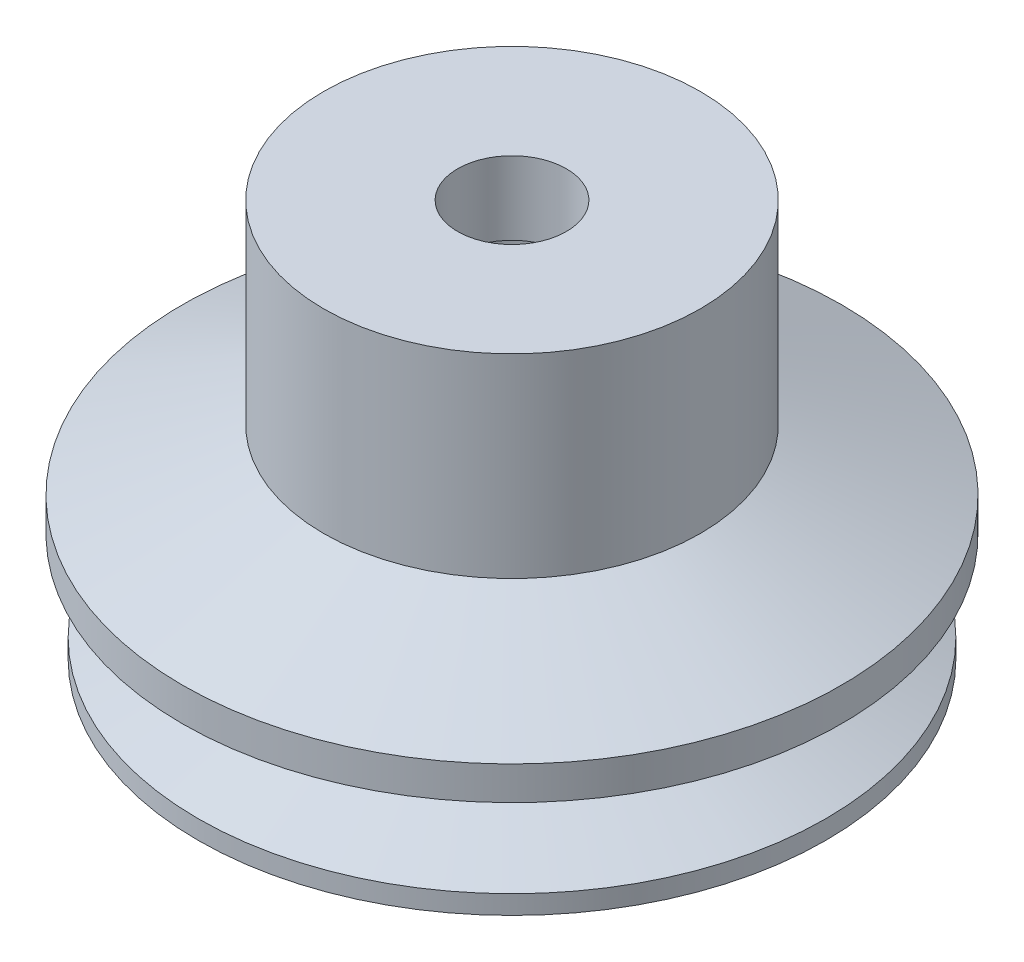
SolidWorks part; units mm, degrees
ref_plane "Plan de face" through (0, 0, 0) normal (0, 0, 1) x (1, 0, 0)
ref_plane "Plan de dessus" through (0, 0, 0) normal (0, 1, 0) x (1, 0, 0)
ref_plane "Plan de droite" through (0, 0, 0) normal (1, 0, 0) x (0, 0, -1)
sketch "Esquisse1" plane through (0, 0, 0) normal (1, 0, 0) x (0, 0, -1)
  line L0 (0, 0) -> (0, 19) construction
  line L19 (-2.6, 19) -> (-2.6, 15.5)
  line L20 (-2.6, 15.5) -> (-3.6, 15.5)
  line L21 (-3.6, 15.5) -> (-3.6, 13.5)
  line L22 (-3.6, 13.5) -> (-2.55, 13.5)
  line L23 (-2.55, 13.5) -> (-2.55, 9)
  line L24 (-2.55, 9) -> (-7.5, 9)
  line L25 (-7.5, 9) -> (-13.75, 6)
  line L26 (-13.75, 6) -> (-7.5, 3.2)
  line L27 (-7.5, 3.2) -> (-15, 0)
  line L28 (-15, 0) -> (-15, 0.9)
  line L29 (-15, 0.9) -> (-9.6111, 3.2)
  line L30 (-9.6111, 3.2) -> (-15.75, 5.2)
  line L32 (-9, 9.7) -> (-9, 19)
  line L33 (-9, 19) -> (-2.6, 19)
  line L34 (-15.75, 5.2) -> (-15.75, 6.8)
  line L35 (-15.75, 6.8) -> (-9, 9.7)
  line L36 (-15.75, 6) -> (-13.75, 6) construction
  line L37 (-7.5, 3.2) -> (-7.5, 9) construction
  dimension "D1" = 19
  dimension "D2" = 9
  dimension "D3" = 15
  dimension "D4" = 0.9
  dimension "D5" = 2.6
  dimension "D6" = 2
  dimension "D7" = 2.55
  dimension "D8" = 3.5
  dimension "D9" = 7.5
  dimension "D11" = 15.75
  dimension "D12" = 3.2
  dimension "D13" = 1.6
  dimension "D14" = 9.3
  dimension "D15" = 6
  dimension "D16" = 2
  dimension "D17" = 3.6
revolve "Révolution1" add sketch "Esquisse1" angle 360 about L0
